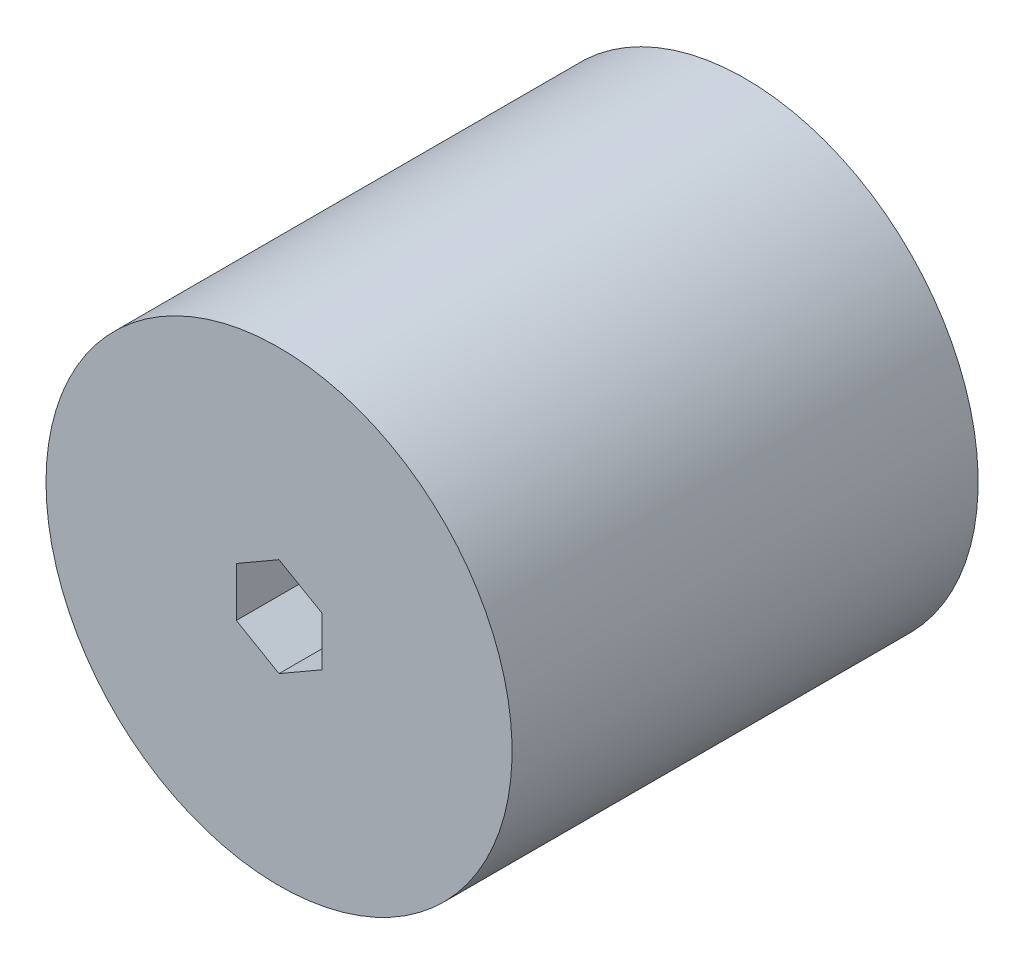
SolidWorks part; units mm, degrees
material "PET"
ref_plane "Front Plane" through (0, 0, 0) normal (0, 0, 1) x (1, 0, 0)
ref_plane "Top Plane" through (0, 0, 0) normal (0, 1, 0) x (1, 0, 0)
ref_plane "Right Plane" through (0, 0, 0) normal (1, 0, 0) x (0, 0, -1)
sketch "Sketch1" plane through (0, 0, 0) normal (0, 0, 1) x (1, 0, 0)
  line L1 (0, 8.0656) -> (-6.985, 4.0328)
  line L2 (-6.985, 4.0328) -> (-6.985, -4.0328)
  line L3 (-6.985, -4.0328) -> (0, -8.0656)
  line L4 (0, -8.0656) -> (6.985, -4.0328)
  line L5 (6.985, -4.0328) -> (6.985, 4.0328)
  line L6 (6.985, 4.0328) -> (0, 8.0656)
  circle A0 centre (0, 0) radius 38.1
  circle A1 centre (0, 0) radius 6.985 construction
  dimension "D1" = 76.2
  dimension "D2" = 13.97
extrude "Boss-Extrude1" add sketch "Sketch1" along normal blind 76.2
